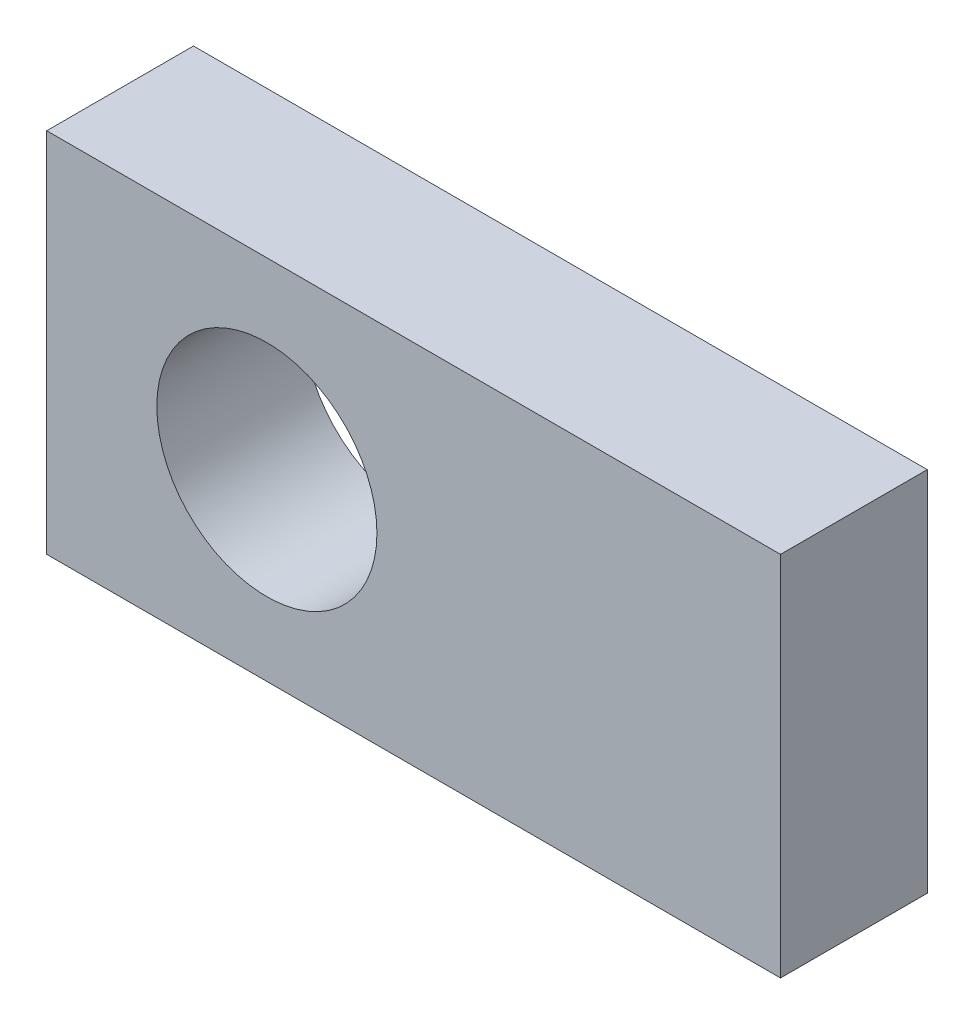
SolidWorks part; units mm, degrees
ref_plane "Front Plane" through (0, 0, 0) normal (0, 0, 1) x (1, 0, 0)
ref_plane "Top Plane" through (0, 0, 0) normal (0, 1, 0) x (1, 0, 0)
ref_plane "Right Plane" through (0, 0, 0) normal (1, 0, 0) x (0, 0, -1)
sketch "Sketch1" plane through (0, 0, 0) normal (0, 0, 1) x (1, 0, 0)
  line L1 (0, 0) -> (20, 0)
  line L2 (0, 0) -> (0, 10)
  line L3 (0, 10) -> (20, 10)
  line L4 (20, 0) -> (20, 10)
  circle A0 centre (6, 5) radius 3
  dimension "D3" = 6
  dimension "D4" = 14
  dimension "D1" = 10
  dimension "D2" = 20
  dimension "D5" = 5
extrude "Boss-Extrude1" add sketch "Sketch1" along normal blind 4
